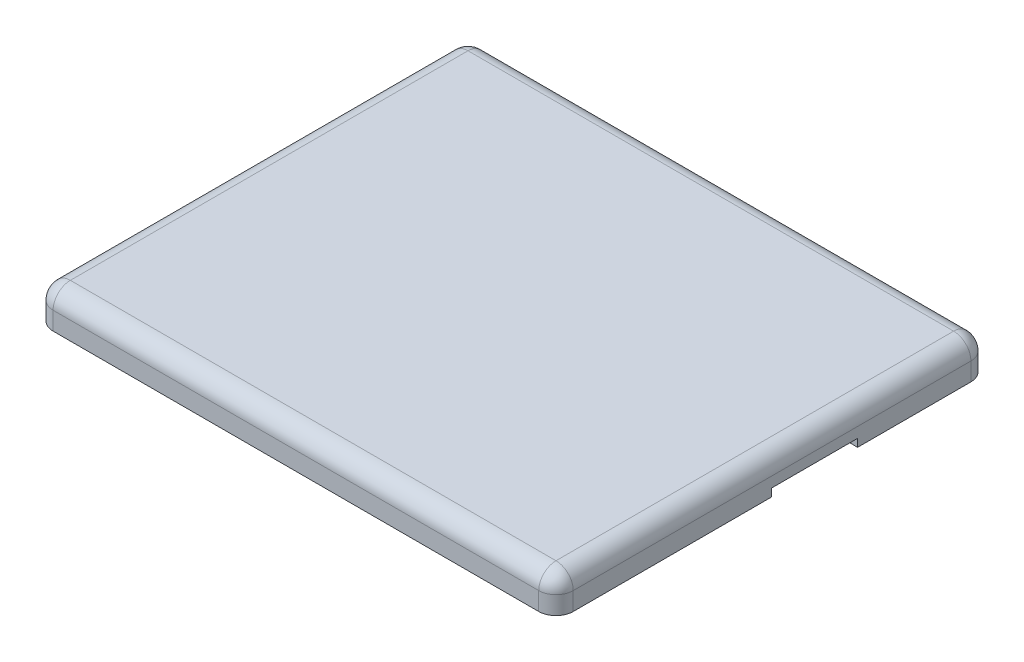
SolidWorks part; units mm, degrees
ref_plane "Front Plane" through (0, 0, 0) normal (0, 0, 1) x (1, 0, 0)
ref_plane "Top Plane" through (0, 0, 0) normal (0, 1, 0) x (1, 0, 0)
ref_plane "Right Plane" through (0, 0, 0) normal (1, 0, 0) x (0, 0, -1)
sketch "Sketch1" plane through (0, 0, 0) normal (0, 1, 0) x (1, 0, 0)
  line L0 (-30.0052, 22.9168) -> (-30.0052, -22.8832) construction
  line L1 (30.15, -25.05) -> (-30.15, -25.05)
  line L2 (30.15, -25.05) -> (30.15, 25.05)
  line L3 (30.15, 25.05) -> (-30.15, 25.05)
  line L4 (-30.15, -25.05) -> (-30.15, 25.05)
  line L5 (30.15, -25.05) -> (-30.15, 25.05) construction
  line L6 (30.15, 25.05) -> (-30.15, -25.05) construction
  line L7 (-28.0052, -24.8832) -> (27.9948, -24.8832) construction
  line L8 (29.9948, 9.9168) -> (29.9948, 22.9168) construction
  point P0 (0, 0)
  dimension "D1" = 60.3
  dimension "D2" = 50.1
  dimension "D3" = 0.1448
  dimension "D4" = 0.1668
  dimension "D5" = 0.1552
extrude "OuterWalls" add sketch "Sketch1" against normal blind 2
sketch "Sketch2" plane through (0, -2, 0) normal (0, -1, 0) x (-1, 0, 0)
  line L0 (28.95, 23.85) -> (28.95, -23.85)
  line L1 (30.15, 25.05) -> (-30.15, 25.05)
  line L2 (30.15, 25.05) -> (30.15, -25.05)
  line L3 (30.15, -25.05) -> (-30.15, -25.05)
  line L4 (-30.15, 25.05) -> (-30.15, -25.05)
  line L5 (28.95, -23.85) -> (-28.95, -23.85)
  line L6 (-28.95, 23.85) -> (-28.95, -23.85)
  line L7 (28.95, 23.85) -> (-28.95, 23.85)
  dimension "D1" = 1.2
extrude "Inner" add sketch "Sketch2" along normal blind 2.1
sketch "Sketch4" plane through (30.15, 0, 0) normal (1, 0, 0) x (0, 0, -1)
  line L0 (-0.0832, -7.6633) -> (-0.0832, -4.2633) construction
  line L1 (-0.0832, -6.9) -> (9.9168, -6.9)
  line L2 (-0.0832, -6.9) -> (-0.0832, -3.2)
  line L3 (-0.0832, -3.2) -> (9.9168, -3.2)
  line L4 (9.9168, -6.9) -> (9.9168, -3.2)
  line L5 (-25.05, 0) -> (25.05, 0) construction
  dimension "D1" = 0
  dimension "D2" = 3.2
  dimension "D3" = 3.7
extrude "Cut-Extrude1" cut sketch "Sketch4" against normal blind 20
fillet "Fillet1" radius 2 8 edges at (30.15, 0, 0) (-30.15, -2.05, 25.05) (-30.15, -2.05, -25.05) (30.15, -2.05, -25.05) (30.15, -2.05, 25.05) (0, 0, 25.05) (-30.15, 0, 0) (0, 0, -25.05)
